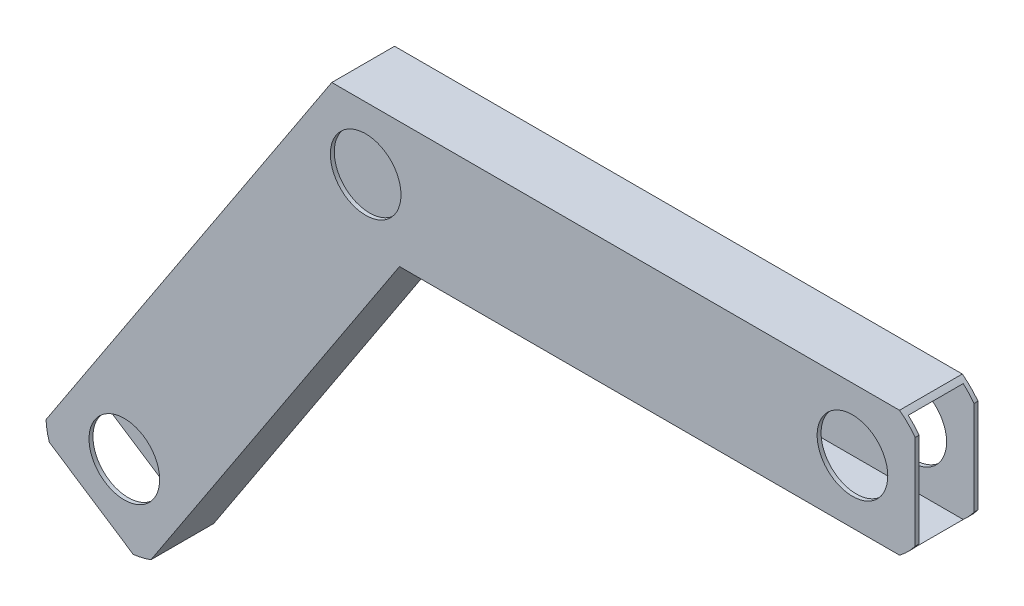
SolidWorks part; units mm, degrees
ref_plane "Front Plane" through (0, 0, 0) normal (0, 0, 1) x (1, 0, 0)
ref_plane "Top Plane" through (0, 0, 0) normal (0, 1, 0) x (1, 0, 0)
ref_plane "Right Plane" through (0, 0, 0) normal (1, 0, 0) x (0, 0, -1)
sketch "Sketch2" plane through (0, 0, 0) normal (0, 0, 1) x (1, 0, 0)
  line L0 (-229.4689, -68.7023) -> (-131.817, 79.8809)
  line L1 (-105.2843, 94.193) -> (91.6848, 94.193)
  line L2 (91.6848, 30.693) -> (-105.2843, 30.693)
  line L3 (-78.7516, 45.0052) -> (-176.4035, -103.578)
  line L4 (-195.1104, -120.4799) -> (-76.5332, 59.9425)
  line L5 (-118.9855, 87.843) -> (117.0848, 87.843)
  line L6 (-118.9855, 87.843) -> (-118.9855, 37.043)
  line L7 (-118.9855, 37.043) -> (117.0848, 37.043)
  line L8 (117.0848, 87.843) -> (117.0848, 37.043)
  line L9 (-195.1104, -120.4799) -> (-237.5628, -92.5794)
  line L10 (-76.5332, 59.9425) -> (-118.9855, 87.843)
  line L11 (-237.5628, -92.5794) -> (-118.9855, 87.843)
  circle A0 centre (-202.9362, -86.1401) radius 31.75
  circle A1 centre (-105.2843, 62.443) radius 31.75
  circle A2 centre (91.6848, 62.443) radius 31.75
  circle A3 centre (-202.9362, -86.1401) radius 14.2875
  circle A4 centre (-105.2843, 62.443) radius 14.2875
  circle A5 centre (91.6848, 62.443) radius 14.2875
  point P21 (-118.9855, 62.443)
  point P22 (117.0848, 62.443)
  dimension "D1" = 63.5
  dimension "D12" = 28.575
  dimension "D2" = 196.9692
  dimension "D3" = 177.8
  dimension "D4" = 329.9674
  dimension "D5" = 50.8
  dimension "D7" = 50.8
  dimension "D8" = 25.4
  dimension "D9" = 215.9
  dimension "D10" = 123.314
  dimension "D11" = 123.314
  dimension "D6" = 25.4
sketch "Sketch3" plane through (0, 0, 0) normal (0, 0, 1) x (1, 0, 0)
  line L0 (-195.1104, -120.4799) -> (-237.5628, -92.5794) construction
  line L1 (-195.1104, -120.4799) -> (-76.5332, 59.9425) construction
  line L2 (-118.9855, 87.843) -> (-118.9855, 37.043) construction
  line L3 (-76.5332, 59.9425) -> (-118.9855, 87.843) construction
  line L4 (-237.5628, -92.5794) -> (-118.9855, 87.843) construction
  line L5 (117.0848, 87.843) -> (117.0848, 37.043) construction
  line L6 (-118.9855, 37.043) -> (117.0848, 37.043) construction
  line L7 (-118.9855, 87.843) -> (117.0848, 87.843) construction
  line L8 (-195.1104, -120.4799) -> (-237.5628, -92.5794)
  line L9 (-195.1104, -120.4799) -> (-76.5332, 59.9425)
  line L10 (-118.9855, 87.843) -> (-118.9855, 37.043)
  line L11 (-76.5332, 59.9425) -> (-118.9855, 87.843)
  line L12 (-237.5628, -92.5794) -> (-118.9855, 87.843)
  line L13 (117.0848, 87.843) -> (117.0848, 37.043)
  line L14 (-118.9855, 37.043) -> (117.0848, 37.043)
  line L15 (-118.9855, 87.843) -> (117.0848, 87.843)
  circle A0 centre (-105.2843, 62.443) radius 14.2875 construction
  circle A1 centre (-105.2843, 62.443) radius 14.2875
  circle A2 centre (-202.9362, -86.1401) radius 14.2875 construction
  circle A3 centre (91.6848, 62.443) radius 14.2875 construction
  circle A4 centre (-202.9362, -86.1401) radius 14.2875
  circle A5 centre (91.6848, 62.443) radius 14.2875
extrude "Boss-Extrude2" add sketch "Sketch3" along normal blind 25.4 contours A1 L10 L12 L8 L9 L14 A4 | A1 L11 L9 L14 L13 L15 A5 | A1 L10 L14 L9 L11 | A1 L11 L10
shell "Shell1" thickness 1.5875
sketch "Sketch4" plane through (-114.1512, -173.6879, 0) normal (-0.5492, -0.8357, 0) x (0.8357, -0.5492, 0)
  line L0 (-98.4662, 23.8125) -> (-146.0912, 23.8125) construction
  line L1 (-146.0912, 23.8125) -> (-146.0912, 1.5875) construction
  line L2 (-98.4662, 1.5875) -> (-146.0912, 1.5875) construction
  line L3 (-98.4662, 23.8125) -> (-98.4662, 1.5875) construction
  line L4 (-98.4662, 23.8125) -> (-146.0912, 23.8125)
  line L5 (-146.0912, 23.8125) -> (-146.0912, 1.5875)
  line L6 (-98.4662, 1.5875) -> (-146.0912, 1.5875)
  line L7 (-98.4662, 23.8125) -> (-98.4662, 1.5875)
extrude "Cut-Extrude1" cut sketch "Sketch4" against normal blind 25.4
sketch "Sketch5" plane through (0, 0, 0) normal (0, 0, 1) x (1, 0, 0)
  circle A0 centre (-202.9362, -86.1401) radius 14.2875 construction
  circle A1 centre (91.6848, 62.443) radius 14.2875 construction
  circle A2 centre (-105.2843, 62.443) radius 14.2875 construction
  circle A3 centre (-202.9362, -86.1401) radius 14.2875
  circle A4 centre (91.6848, 62.443) radius 14.2875
  circle A5 centre (-105.2843, 62.443) radius 14.2875
extrude "Cut-Extrude2" cut sketch "Sketch5" along normal through all
sketch "Sketch6" plane through (0, 0, 25.4) normal (0, 0, 1) x (1, 0, 0)
  line L6 (117.0848, 87.843) -> (-118.9855, 87.843)
  line L7 (-118.9855, 87.843) -> (-237.5628, -92.5794)
  line L8 (-237.5628, -92.5794) -> (-195.1104, -120.4799)
  line L9 (-195.1104, -120.4799) -> (-91.5832, 37.043)
  line L10 (-91.5832, 37.043) -> (117.0848, 37.043)
  line L11 (117.0848, 37.043) -> (117.0848, 87.843)
  line L12 (117.0848, 87.843) -> (-118.9855, 87.843)
  line L13 (-118.9855, 87.843) -> (-237.5628, -92.5794)
  line L14 (-237.5628, -92.5794) -> (-195.1104, -120.4799)
  line L15 (-195.1104, -120.4799) -> (-91.5832, 37.043)
  line L16 (-91.5832, 37.043) -> (117.0848, 37.043)
  line L17 (117.0848, 37.043) -> (117.0848, 87.843)
  circle A0 centre (-202.9362, -86.1401) radius 14.2875 construction
  circle A1 centre (-202.9362, -86.1401) radius 14.2875
  circle A2 centre (-202.9362, -86.1401) radius 31.75
  circle A3 centre (91.6848, 62.443) radius 14.2875 construction
  circle A4 centre (91.6848, 62.443) radius 14.2875
  circle A5 centre (91.6848, 62.443) radius 31.75
  line M12 (117.0848, 87.843) -> (-118.9855, 87.843)
  line M13 (-118.9855, 87.843) -> (-237.5628, -92.5794)
  line M14 (-237.5628, -92.5794) -> (-195.1104, -120.4799)
  line M15 (-195.1104, -120.4799) -> (-91.5832, 37.043)
  line M16 (-91.5832, 37.043) -> (117.0848, 37.043)
  line M17 (117.0848, 37.043) -> (117.0848, 87.843)
  dimension "D1" = 0
extrude "Cut-Extrude4" cut sketch "Sketch6" against normal blind 25.4 contours A5 M17 M12 | A5 M16 M17 | A2 M13 M14 | A2 M14 M15
equation "\"D10@Sketch2\"=\"D11@Sketch2\""
